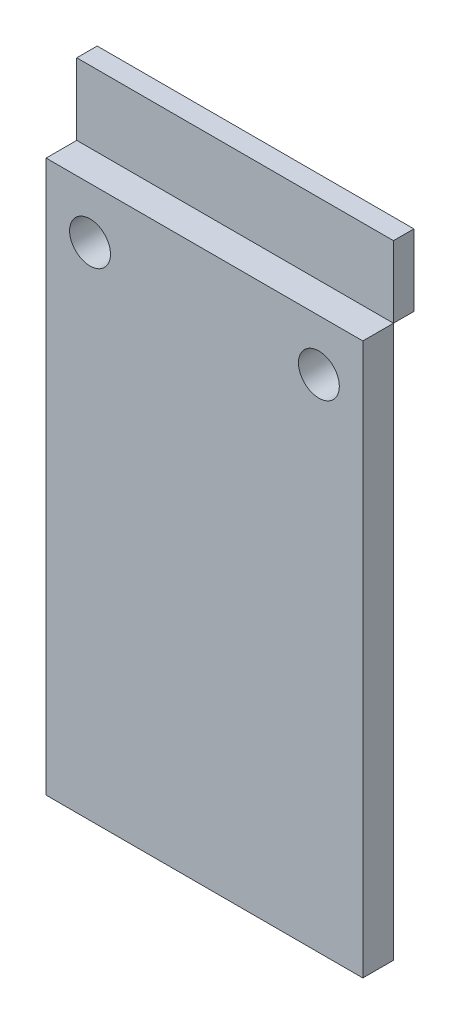
SolidWorks part; units mm, degrees
ref_plane "Płaszczyzna przednia" through (0, 0, 0) normal (0, 0, 1) x (1, 0, 0)
ref_plane "Płaszczyzna górna" through (0, 0, 0) normal (0, 1, 0) x (1, 0, 0)
ref_plane "Płaszczyzna prawa" through (0, 0, 0) normal (1, 0, 0) x (0, 0, -1)
sketch "Szkic1" plane through (0, 0, 0) normal (0, 0, 1) x (1, 0, 0)
  line L0 (0, 13.5) -> (0, -13.5) construction
  line L1 (-7.75, 13.5) -> (7.75, 13.5)
  line L2 (-7.75, 13.5) -> (-7.75, -13.5)
  line L3 (-7.75, -13.5) -> (7.75, -13.5)
  line L4 (7.75, 13.5) -> (7.75, -13.5)
  line L5 (-7.75, 13.5) -> (7.75, -13.5) construction
  line L6 (-7.75, -13.5) -> (7.75, 13.5) construction
  circle A0 centre (-5.6, 11) radius 1
  circle A1 centre (5.6, 11) radius 1
  point P0 (0, 0)
  point P10 (0, 0)
  dimension "D3" = 2
  dimension "D1" = 15.5
  dimension "D2" = 27
  dimension "D4" = 2.5
  dimension "D5" = 11.2
extrude "Dodanie-wyciągnięcie1" add sketch "Szkic1" along normal blind 1.5
sketch "Szkic2" plane through (0, 0, 0) normal (0, 0, -1) x (-1, 0, 0)
  line L1 (-7.75, 13.5) -> (7.75, 13.5)
  line L2 (-7.75, 13.5) -> (-7.75, 17)
  line L3 (-7.75, 17) -> (7.75, 17)
  line L4 (7.75, 13.5) -> (7.75, 17)
  point P5 (0, 0)
  dimension "D1" = 3.5
extrude "Dodanie-wyciągnięcie2" add sketch "Szkic2" along normal blind 1 separate body
